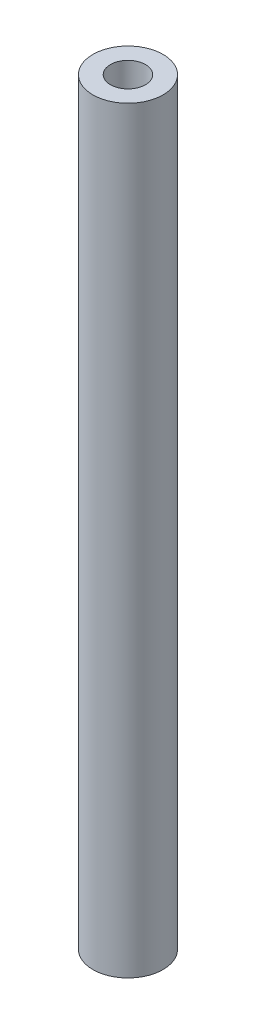
SolidWorks part; units mm, degrees
material "6061-O (SS)"
ref_plane "Alzado" through (0, 0, 0) normal (0, 0, 1) x (1, 0, 0)
ref_plane "Planta" through (0, 0, 0) normal (0, 1, 0) x (1, 0, 0)
ref_plane "Vista lateral" through (0, 0, 0) normal (1, 0, 0) x (0, 0, -1)
sketch "Croquis1" plane through (0, 0, 0) normal (0, 1, 0) x (1, 0, 0)
  circle A0 centre (0, 0) radius 5
  dimension "D1" = 10
extrude "Saliente-Extruir1" add sketch "Croquis1" along normal blind 108
ref_plane "Plano1" through (0, 54, 0) normal (0, -1, 0) x (-1, 0, 0)
sketch "Croquis2" plane through (0, 0, 0) normal (0, -1, 0) x (1, 0, 0)
  circle A0 centre (0, 0) radius 2.5
  dimension "D1" = 5
extrude "Cortar-Extruir1" cut sketch "Croquis2" against normal blind 10
mirror "Simetría1" about plane through (0, 54, 0) normal (0, -1, 0) of "Cortar-Extruir1"
